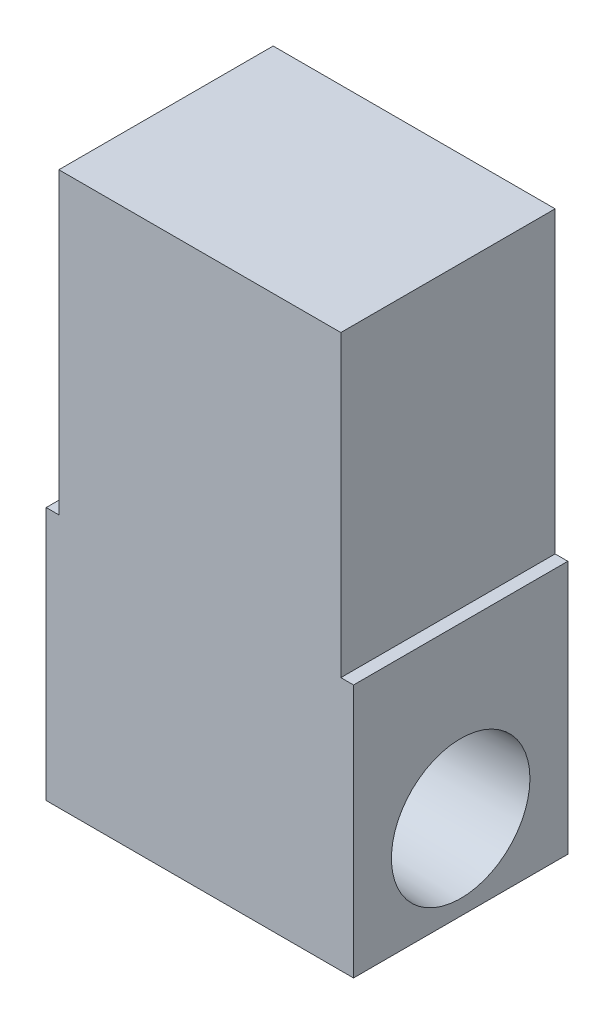
SolidWorks part; units mm, degrees
ref_plane "Front Plane" through (0, 0, 0) normal (0, 0, 1) x (1, 0, 0)
ref_plane "Top Plane" through (0, 0, 0) normal (0, 1, 0) x (1, 0, 0)
ref_plane "Right Plane" through (0, 0, 0) normal (1, 0, 0) x (0, 0, -1)
sketch "Sketch1" plane through (0, 0, 0) normal (0, 0, 1) x (1, 0, 0)
  line L0 (0, -15.494) -> (0, 38.354) construction
  line L1 (-13.843, -11.43) -> (13.843, -11.43)
  line L2 (-13.843, -11.43) -> (-13.843, 11.43)
  line L3 (-13.843, 11.43) -> (13.843, 11.43)
  line L4 (13.843, -11.43) -> (13.843, 11.43)
  line L5 (-13.843, -11.43) -> (13.843, 11.43) construction
  line L6 (-13.843, 11.43) -> (13.843, -11.43) construction
  line L7 (-12.7, 11.43) -> (12.7, 11.43)
  line L8 (-12.7, 11.43) -> (-12.7, 38.354)
  line L9 (-12.7, 38.354) -> (12.7, 38.354)
  line L10 (12.7, 11.43) -> (12.7, 38.354)
  point P0 (0, 0)
  point P13 (0, 11.43)
  dimension "D1" = 27.686
  dimension "D2" = 22.86
  dimension "D3" = 25.4
  dimension "D4" = 12.7
  dimension "D5" = 26.924
extrude "Boss-Extrude1" add sketch "Sketch1" along normal blind 19.304 contours L1 L4 L3 L2 | L3 L10 L9 L8
hole_wizard "1/4 NPT Tapped Hole1" positions "3DSketch2" profile "Sketch3" size "1/4" standard "ANSI Inch"
sketch3d "3DSketch2"
  line L0 (13.843, -11.43, 19.304) -> (13.843, -11.43, 0) construction
  line L1 (13.843, -11.43, 19.304) -> (13.843, 11.43, 19.304) construction
  point P0 (13.843, -3.81, 9.652)
  dimension "D1" = 7.62
  dimension "D2" = 9.652
cosmetic thread "Hole Thread1" parameters "D1"=9.906, "D2"=13.7092
sketch "Sketch3" plane through (13.843, -3.81, 9.652) normal (0, 1, 0) x (0, 0, -1)
  line L0 (0, 0) -> (0, 13.5023)
  line L1 (5.5626, 10.16) -> (0, 13.5023)
  line L2 (-5.5626, 10.16) -> (0, 13.5023) construction
  line L3 (5.5626, 10.16) -> (5.5626, 9.906)
  line L4 (5.5626, 9.906) -> (5.9437, 9.906)
  line L5 (5.9437, 9.906) -> (6.2403, 0)
  line L6 (-5.9437, 9.906) -> (-6.2403, 0) construction
  line L7 (6.2403, 0) -> (0, 0)
  line L8 (0, -6.35) -> (0, 107.95) construction
  line L11 (-5.5626, 9.906) -> (-5.9437, 9.906) construction
  dimension "Tap Drill Dia." = 11.1252
  dimension "Tap Drill Depth" = 10.16
  dimension "Thread Dia." = 12.4806
  dimension "Thread Angle" = 3.43
  dimension "Thread Depth" = 9.906
  dimension "Drill Angle" = 118
hole_wizard "1/4 NPT Tapped Hole2" positions "3DSketch3" profile "Sketch4" size "1/4" standard "ANSI Inch"
sketch3d "3DSketch3"
  line L0 (-13.843, -11.43, 0) -> (-13.843, 11.43, 0) construction
  line L1 (-13.843, -11.43, 19.304) -> (-13.843, -11.43, 0) construction
  point P0 (-13.843, -3.81, 9.652)
  dimension "D1" = 9.652
  dimension "D2" = 7.62
sketch "Sketch4" plane through (-13.843, -3.81, 9.652) normal (0, 1, 0) x (0, 0, 1)
  line L0 (0, 0) -> (0, 13.5023)
  line L1 (5.5626, 10.16) -> (0, 13.5023)
  line L2 (-5.5626, 10.16) -> (0, 13.5023) construction
  line L3 (5.5626, 10.16) -> (5.5626, 9.906)
  line L4 (5.5626, 9.906) -> (5.9437, 9.906)
  line L5 (5.9437, 9.906) -> (6.2403, 0)
  line L6 (-5.9437, 9.906) -> (-6.2403, 0) construction
  line L7 (6.2403, 0) -> (0, 0)
  line L8 (0, -6.35) -> (0, 107.95) construction
  line L11 (-5.5626, 9.906) -> (-5.9437, 9.906) construction
  dimension "Tap Drill Dia." = 11.1252
  dimension "Tap Drill Depth" = 10.16
  dimension "Thread Dia." = 12.4806
  dimension "Thread Angle" = 3.43
  dimension "Thread Depth" = 9.906
  dimension "Drill Angle" = 118
cosmetic thread "Hole Thread2" parameters "D1"=9.906, "D2"=13.7092
